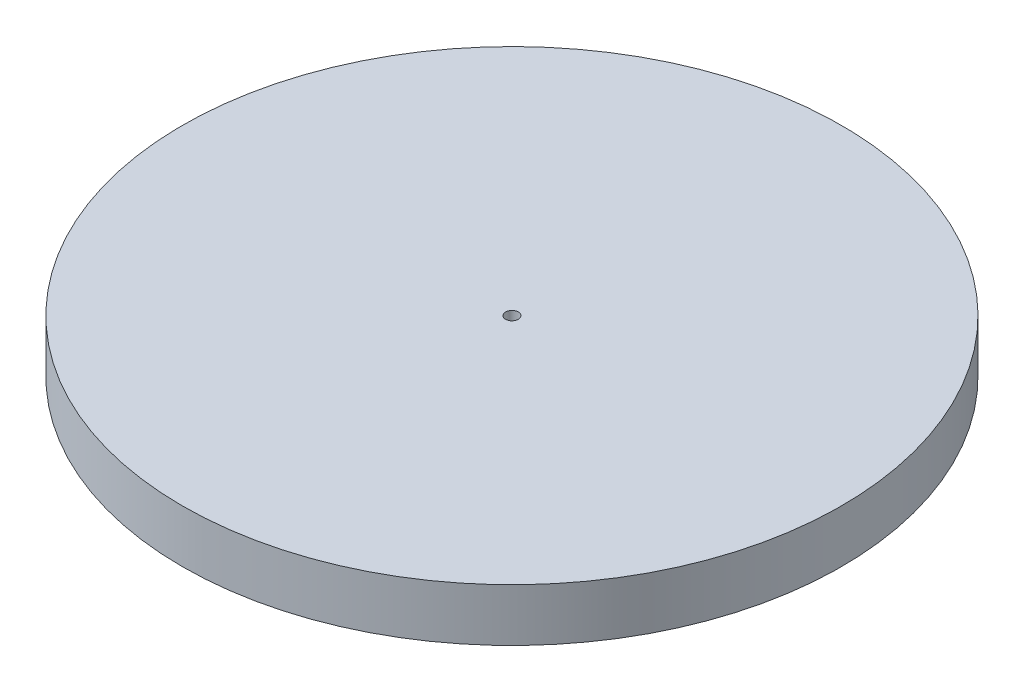
SolidWorks part; units mm, degrees
ref_plane "Front Plane" through (0, 0, 0) normal (0, 0, 1) x (1, 0, 0)
ref_plane "Top Plane" through (0, 0, 0) normal (0, 1, 0) x (1, 0, 0)
ref_plane "Right Plane" through (0, 0, 0) normal (1, 0, 0) x (0, 0, -1)
sketch "Sketch3" plane through (0, 0, 0) normal (0, 0, 1) x (1, 0, 0)
  line L0 (30, 21.1926) -> (30, 40) construction
  line L1 (30, 40) -> (0, 40) construction
  line L2 (0, 40) -> (0, 0) construction
  line L4 (1.2, 40) -> (1.2, 35)
  line L5 (1.2, 35) -> (0, 35)
  line L6 (0, 35) -> (0, 0)
  line L7 (30, 21.1926) -> (33, 21.1926) construction
  line L8 (33, 21.1926) -> (33, 40) construction
  line L10 (30, 21.1926) -> (30, 22.1926)
  line L11 (30, 22.1926) -> (32, 22.1926)
  line L12 (1.2, 40) -> (62, 40)
  line L14 (62, 30.0951) -> (62, 40)
  spline S0 degree 4 poles (-2.34, 2.5369) (-2.2911, 2.3994) (-2.1888, 2.1261) (-2.0104, 1.6993) (-1.7697, 1.2381) (-1.5307, 0.8781) (-1.3184, 0.6284) (-1.1777, 0.4871) (-1.0418, 0.3716) (-0.9146, 0.2798) (-0.7901, 0.205) (-0.6712, 0.1456) (-0.5526, 0.0978) (-0.4376, 0.0608) (-0.3314, 0.0357) (-0.2421, 0.0196) (-0.1593, 0.0096) (-0.1034, 0.0041) (-0.0165, 0) (0.0256, -0.0006) (0.1246, 0.0003) (0.188, 0.0048) (0.3022, 0.0143) (0.4349, 0.0337) (0.5916, 0.0646) (0.7584, 0.109) (0.9485, 0.1679) (1.1484, 0.2408) (1.372, 0.3337) (1.6163, 0.448) (1.8495, 0.5662) (2.0879, 0.6955) (2.3321, 0.8352) (2.5818, 0.9851) (2.8375, 1.1445) (3.2809, 1.4299) (3.9872, 1.9089) (4.7829, 2.479) (5.6702, 3.1358) (6.9521, 4.1026) (8.5426, 5.3258) (10.6042, 6.9256) (12.8266, 8.643) (14.7393, 10.108) (16.6561, 11.5628) (18.2636, 12.7702) (19.8694, 13.9632) (21.4946, 15.1564) (22.7795, 16.0923) (24.105, 17.0476) (25.3718, 17.9541) (27.0889, 19.1685) (28.4196, 20.1024) (29.9254, 21.1412) (30.4116, 21.4766) (30.868, 21.7927) (30.8606, 21.7877) (30.8423, 21.7751) (30.834, 21.7694) (30.8389, 21.7728) (30.8566, 21.7851) (30.8846, 21.8046) (30.9115, 21.8233) (30.9317, 21.8373) (30.9485, 21.849) (30.9656, 21.8609) (30.983, 21.8731) (31.0038, 21.8876) (31.0335, 21.9083) (31.0688, 21.9329) (31.1041, 21.9576) (31.1394, 21.9823) (31.1688, 22.0029) (31.1923, 22.0194) (31.2335, 22.0483) (31.3158, 22.1061) (31.439, 22.193) (31.603, 22.3095) (31.7897, 22.4436) (31.9754, 22.579) (32.2063, 22.75) (32.435, 22.924) (32.6607, 23.1018) (32.8383, 23.2477) (32.9263, 23.3217) (32.97, 23.359) knots 0 0 0 0 0 0.013197 0.026395 0.041801 0.046986 0.052172 0.055998 0.059825 0.063091 0.066357 0.069107 0.071856 0.074605 0.077354 0.078823 0.080291 0.08176 0.083228 0.084967 0.086705 0.088444 0.090182 0.094716 0.09925 0.102596 0.105942 0.112635 0.118542 0.124449 0.130357 0.136264 0.143077 0.14989 0.156704 0.163517 0.190769 0.227073 0.245225 0.263376 0.335983 0.40859 0.481197 0.5175 0.553804 0.626411 0.662714 0.699018 0.735321 0.771625 0.807928 0.844231 0.916838 0.937629 0.938278 0.938603 0.938928 0.939578 0.939903 0.940228 0.940877 0.941527 0.942177 0.942826 0.943151 0.943476 0.944126 0.944775 0.945425 0.946725 0.948024 0.948674 0.949323 0.949973 0.950623 0.953222 0.958419 0.963617 0.968814 0.974012 0.97921 0.989605 0.994802 1 1 1 1 1 construction
  spline S1 degree 4 poles (0, 0) (0.016, -0.0003) (0.0474, -0.0004) (0.1246, 0.0003) (0.188, 0.0048) (0.3022, 0.0143) (0.4349, 0.0337) (0.5916, 0.0646) (0.7584, 0.109) (0.9485, 0.1679) (1.1484, 0.2408) (1.372, 0.3337) (1.6163, 0.448) (1.8495, 0.5662) (2.0879, 0.6955) (2.3321, 0.8352) (2.5818, 0.9851) (2.8375, 1.1445) (3.2809, 1.4299) (3.9872, 1.9089) (4.7829, 2.479) (5.6702, 3.1358) (6.9521, 4.1026) (8.5426, 5.3258) (10.6042, 6.9256) (12.8266, 8.643) (14.7393, 10.108) (16.6561, 11.5628) (18.2636, 12.7702) (19.8694, 13.9632) (21.4946, 15.1564) (22.7795, 16.0923) (24.105, 17.0476) (25.3718, 17.9541) (27.0889, 19.1685) (28.2529, 19.9854) (29.4493, 20.8125) (30, 21.1926) knots 0.083228 0.083228 0.083228 0.083228 0.083228 0.084967 0.086705 0.088444 0.090182 0.094716 0.09925 0.102596 0.105942 0.112635 0.118542 0.124449 0.130357 0.136264 0.143077 0.14989 0.156704 0.163517 0.190769 0.227073 0.245225 0.263376 0.335983 0.40859 0.481197 0.5175 0.553804 0.626411 0.662714 0.699018 0.735321 0.771625 0.807928 0.844231 0.916838 0.916838 0.916838 0.916838 0.916838
  spline S2 degree 4 poles (28.9914, 21.4654) (29.092, 21.4893) (29.2878, 21.536) (29.5826, 21.6057) (30.2265, 21.7608) (30.7023, 21.875) (31.7588, 22.1331) (32.1999, 22.2416) (33.2632, 22.5047) (33.8994, 22.6641) (34.7645, 22.8812) (35.5999, 23.093) (36.6077, 23.3496) (37.666, 23.6214) (38.8423, 23.9254) (40.0087, 24.2289) (41.2779, 24.5609) (42.8555, 24.9759) (44.6858, 25.4601) (46.8779, 26.0435) (49.139, 26.6478) (51.5788, 27.3017) (53.7334, 27.8802) (56.3517, 28.5827) (58.2069, 29.0808) (61.0383, 29.8383) (62.1979, 30.1481) (63.5094, 30.4977) (64.5878, 30.7852) (64.6875, 30.8115) (64.9851, 30.8908) knots 0 0 0 0 0 0.009964 0.019928 0.039351 0.058773 0.083003 0.104635 0.126266 0.147897 0.169528 0.191651 0.224098 0.256544 0.288991 0.321438 0.353884 0.398192 0.463085 0.527978 0.592872 0.657765 0.722658 0.787552 0.852445 0.917338 0.958669 0.979335 1 1 1 1 1 construction
  spline S3 degree 4 poles (32, 22.1926) (32.1629, 22.2327) (32.489, 22.3131) (33.2632, 22.5047) (33.8994, 22.6641) (34.7645, 22.8812) (35.5999, 23.093) (36.6077, 23.3496) (37.666, 23.6214) (38.8423, 23.9254) (40.0087, 24.2289) (41.2779, 24.5609) (42.8555, 24.9759) (44.6858, 25.4601) (46.8779, 26.0435) (49.139, 26.6478) (51.5788, 27.3017) (53.7334, 27.8802) (56.3517, 28.5827) (58.2069, 29.0808) (60.5425, 29.7056) (61.5137, 29.9653) (62, 30.0951) knots 0.083003 0.083003 0.083003 0.083003 0.083003 0.104635 0.126266 0.147897 0.169528 0.191651 0.224098 0.256544 0.288991 0.321438 0.353884 0.398192 0.463085 0.527978 0.592872 0.657765 0.722658 0.787552 0.852445 0.917338 0.917338 0.917338 0.917338 0.917338
  point P12 (62, 44.6568)
  dimension "D1" = 1
  dimension "D2" = 1.2
  dimension "D3" = 5
  dimension "D4" = 3
  dimension "D5" = 30
  dimension "D6" = 21.1926
  dimension "D7" = 30
  dimension "D8" = 40
  dimension "D9" = 30
  dimension "D10" = 2
revolve "Revolve4" add sketch "Sketch3" angle 360 about L2
sketch "Sketch5" plane through (0, 40, 0) normal (0, 1, 0) x (1, 0, 0)
  circle A0 centre (0, 0) radius 1.2
  circle A1 centre (0, 0) radius 1.2 construction
extrude "Cut-Extrude1" cut sketch "Sketch5" against normal through all
ref_plane "Plane1" through (0, 0.2638, 0) normal (0, -1, 0) x (-1, 0, 0)
sketch "Sketch6" plane through (0, 0.2638, 0) normal (0, -1, 0) x (-1, 0, 0)
  circle A0 centre (0, 0) radius 1.2 construction
  point P0 (0, 0)
